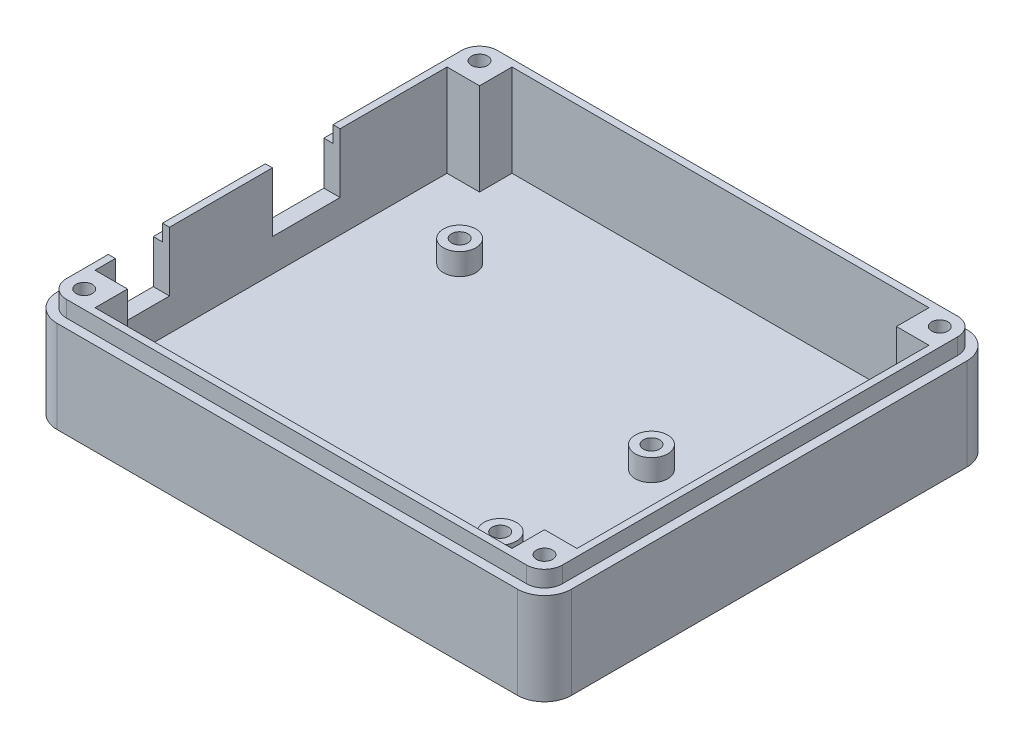
SolidWorks part; units mm, degrees
ref_plane "Front" through (0, 0, 0) normal (0, 0, 1) x (1, 0, 0)
ref_plane "Top" through (0, 0, 0) normal (0, 1, 0) x (1, 0, 0)
ref_plane "Right" through (0, 0, 0) normal (1, 0, 0) x (0, 0, -1)
sketch "Sketch1" plane through (0, 0, 0) normal (0, 1, 0) x (1, 0, 0)
  line L1 (0, 0) -> (95, 0)
  line L2 (0, 0) -> (0, 83)
  line L3 (0, 83) -> (95, 83)
  line L4 (95, 0) -> (95, 83)
  dimension "D1" = 83
  dimension "D2" = 95
extrude "Boss-Extrude1" add sketch "Sketch1" along normal blind 3
sketch "Sketch2" plane through (0, 3, 0) normal (0, 1, 0) x (1, 0, 0)
  line L5 (0, 83) -> (95, 83)
  line L6 (0, 83) -> (0, 0)
  line L7 (0, 0) -> (95, 0)
  line L8 (3, 80) -> (3, 3)
  line L9 (3, 3) -> (92, 3)
  line L10 (92, 3) -> (92, 80)
  line L11 (92, 80) -> (3, 80)
  line L12 (3, 80) -> (3, 3)
  line L13 (3, 3) -> (92, 3)
  line L14 (92, 3) -> (92, 80)
  line L15 (92, 80) -> (3, 80)
  line L16 (95, 83) -> (95, 0)
  dimension "D1" = 3
extrude "Boss-Extrude2" add sketch "Sketch2" along normal blind 17
sketch "Sketch4" plane through (0, 3, 0) normal (0, 1, 0) x (1, 0, 0)
  line L0 (3, 3) -> (92, 3) construction
  line L1 (3, 80) -> (3, 3) construction
  circle A0 centre (17.3, 12.5) radius 3
  circle A1 centre (18.57, 60.76) radius 3
  circle A2 centre (69.24, 45.52) radius 3
  circle A3 centre (69.24, 17.58) radius 3
  dimension "D2" = 6
  dimension "D3" = 6
  dimension "D4" = 6
  dimension "D5" = 6
  dimension "D1" = 9.5
  dimension "D6" = 14.3
  dimension "D7" = 1.27
  dimension "D8" = 48.26
  dimension "D9" = 51.94
  dimension "D10" = 5.08
  dimension "D11" = 27.94
extrude "Boss-Extrude3" add sketch "Sketch4" along normal blind 4
sketch "Sketch5" plane through (0, 7, 0) normal (0, 1, 0) x (1, 0, 0)
  circle A0 centre (18.57, 60.76) radius 1.5
  circle A1 centre (69.24, 45.52) radius 1.5
  circle A2 centre (69.24, 17.58) radius 1.5
  circle A3 centre (17.3, 12.5) radius 1.5
  dimension "D1" = 3
  dimension "D2" = 3
  dimension "D3" = 3
  dimension "D4" = 3
extrude "Cut-Extrude2" cut sketch "Sketch5" against normal up to surface (7 mm away) up to face at (47.5, 0, -41.5)
sketch "Sketch6" plane through (0, 3, 0) normal (0, 1, 0) x (1, 0, 0)
  line L1 (3, 3) -> (9, 3)
  line L2 (3, 3) -> (3, 9)
  line L3 (3, 9) -> (9, 9)
  line L4 (9, 3) -> (9, 9)
  line L5 (92, 3) -> (86, 3)
  line L6 (92, 3) -> (92, 9)
  line L7 (92, 9) -> (86, 9)
  line L8 (86, 3) -> (86, 9)
  line L9 (92, 80) -> (86, 80)
  line L10 (92, 80) -> (92, 74)
  line L11 (92, 74) -> (86, 74)
  line L12 (86, 80) -> (86, 74)
  line L13 (3, 80) -> (9, 80)
  line L14 (3, 80) -> (3, 74)
  line L15 (3, 74) -> (9, 74)
  line L16 (9, 80) -> (9, 74)
  dimension "D1" = 6
  dimension "D2" = 6
  dimension "D3" = 6
  dimension "D4" = 6
extrude "Boss-Extrude4" add sketch "Sketch6" along normal up to surface (17 mm away) up to face at (47.5, 20, -41.5)
sketch "Sketch7" plane through (0, 20, 0) normal (0, 1, 0) x (1, 0, 0)
  line L2 (9, 3) -> (9, 9) construction
  line L4 (9, 9) -> (3, 9) construction
  line L5 (86, 9) -> (86, 3) construction
  line L6 (92, 9) -> (86, 9) construction
  line L7 (86, 74) -> (92, 74) construction
  line L8 (86, 80) -> (86, 74) construction
  line L9 (9, 74) -> (9, 80) construction
  line L10 (3, 74) -> (9, 74) construction
  circle A0 centre (5, 5) radius 1.5
  circle A1 centre (90, 5) radius 1.5
  circle A2 centre (90, 78) radius 1.5
  circle A3 centre (5, 78) radius 1.5
  dimension "D1" = 3
  dimension "D4" = 3
  dimension "D7" = 3
  dimension "D10" = 3
  dimension "D2" = 4
  dimension "D3" = 4
  dimension "D5" = 4
  dimension "D6" = 4
  dimension "D8" = 4
  dimension "D9" = 4
  dimension "D11" = 4
  dimension "D12" = 4
extrude "Cut-Extrude3" cut sketch "Sketch7" against normal up to surface (20 mm away) up to face at (69.24, 0, -47.02)
fillet "Fillet4" radius 5 4 edges at (95, 10, -83) (0, 10, -83) (95, 10, 0) (0, 10, 0)
sketch "Sketch9" plane through (0, 20, 0) normal (0, 1, 0) x (1, 0, 0)
  line L4 (95, 5) -> (95, 78)
  line L5 (90, 83) -> (5, 83)
  line L6 (0, 78) -> (0, 5)
  line L7 (5, 0) -> (90, 0)
  line L8 (93.3, 5) -> (93.3, 78)
  line L9 (5, 1.7) -> (90, 1.7)
  line L10 (1.7, 78) -> (1.7, 5)
  line L11 (90, 81.3) -> (5, 81.3)
  line L12 (93.3, 5) -> (93.3, 78)
  line L13 (5, 1.7) -> (90, 1.7)
  line L14 (1.7, 78) -> (1.7, 5)
  line L15 (90, 81.3) -> (5, 81.3)
  arc A4 (95, 78) -> (90, 83) centre (90, 78) ccw
  arc A5 (5, 83) -> (0, 78) centre (5, 78) ccw
  arc A6 (0, 5) -> (5, 0) centre (5, 5) ccw
  arc A7 (90, 0) -> (95, 5) centre (90, 5) ccw
  arc A8 (93.3, 78) -> (90, 81.3) centre (90, 78) ccw
  arc A9 (90, 1.7) -> (93.3, 5) centre (90, 5) ccw
  arc A10 (1.7, 5) -> (5, 1.7) centre (5, 5) ccw
  arc A11 (5, 81.3) -> (1.7, 78) centre (5, 78) ccw
  arc A12 (93.3, 78) -> (90, 81.3) centre (90, 78) ccw
  arc A13 (90, 1.7) -> (93.3, 5) centre (90, 5) ccw
  arc A14 (1.7, 5) -> (5, 1.7) centre (5, 5) ccw
  arc A15 (5, 81.3) -> (1.7, 78) centre (5, 78) ccw
  dimension "D1" = 1.7
  dimension "D2" = 1.7
extrude "Cut-Extrude4" cut sketch "Sketch9" against normal blind 3
sketch "Sketch3" plane through (3, 0, 0) normal (1, 0, 0) x (0, 0, -1)
  line L0 (3, 20) -> (3, 3) construction
  line L1 (12.75, 9) -> (22.75, 9)
  line L2 (12.75, 9) -> (12.75, 20)
  line L3 (12.75, 20) -> (22.75, 20)
  line L4 (22.75, 9) -> (22.75, 20)
  line L6 (74, 3) -> (9, 3) construction
  line L7 (41.75, 20) -> (54.25, 20)
  line L8 (41.75, 20) -> (41.75, 9)
  line L9 (41.75, 9) -> (54.25, 9)
  line L10 (54.25, 20) -> (54.25, 9)
  dimension "D1" = 9.75
  dimension "D2" = 10
  dimension "D3" = 19
  dimension "D4" = 12.5
  dimension "D5" = 6
  dimension "D6" = 11
extrude "Cut-Extrude1" cut sketch "Sketch3" against normal up to surface (3 mm away) up to face at (0, 8.5, -41.5)
